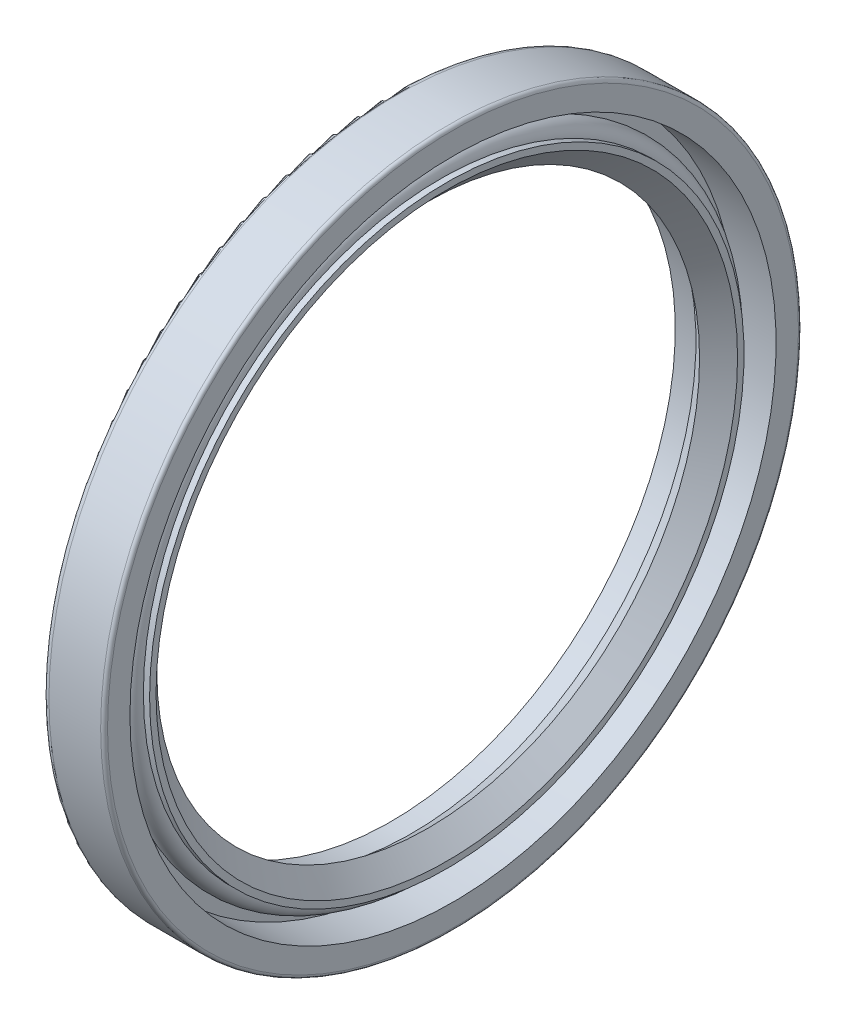
SolidWorks part; units mm, degrees
ref_plane "Piano frontale" through (0, 0, 0) normal (0, 0, 1) x (1, 0, 0)
ref_plane "Piano superiore" through (0, 0, 0) normal (0, 1, 0) x (1, 0, 0)
ref_plane "Piano destro" through (0, 0, 0) normal (1, 0, 0) x (0, 0, -1)
ref_plane "Piano1" through (0, 0, 0) normal (0, 0, 1) x (1, 0, 0)
sketch "Schizzo1" plane through (0, 0, 0) normal (0, 0, 1) x (1, 0, 0)
  line L0 (0, 66.1667) -> (0, 55)
  line L1 (0, 55) -> (4, 55)
  line L2 (4, 55) -> (7.2, 52.5)
  line L3 (7.2, 52.5) -> (10.8, 56.25)
  line L4 (10.8, 56.25) -> (10.8, 57.5)
  line L5 (10.8, 57.5) -> (9.6, 57.5)
  line L6 (4.8, 57.5) -> (4, 57.5)
  line L7 (4, 57.5) -> (4, 62.5)
  line L8 (4, 62.5) -> (12, 62.5)
  line L9 (12, 62.5) -> (12, 66.8333)
  line L10 (11.3333, 67.5) -> (1.3333, 67.5)
  line L11 (11.3333, 0) -> (1.3333, 0) construction
  arc A0 (9.6, 57.5) -> (4.8, 57.5) centre (7.2, 57.5) ccw
  arc A1 (12, 66.8333) -> (11.3333, 67.5) centre (11.3333, 66.8333) ccw
  arc A2 (1.3333, 67.5) -> (0, 66.1667) centre (1.3333, 66.1667) ccw
revolve "Rivoluzione1" add sketch "Schizzo1" angle 360 about L11
